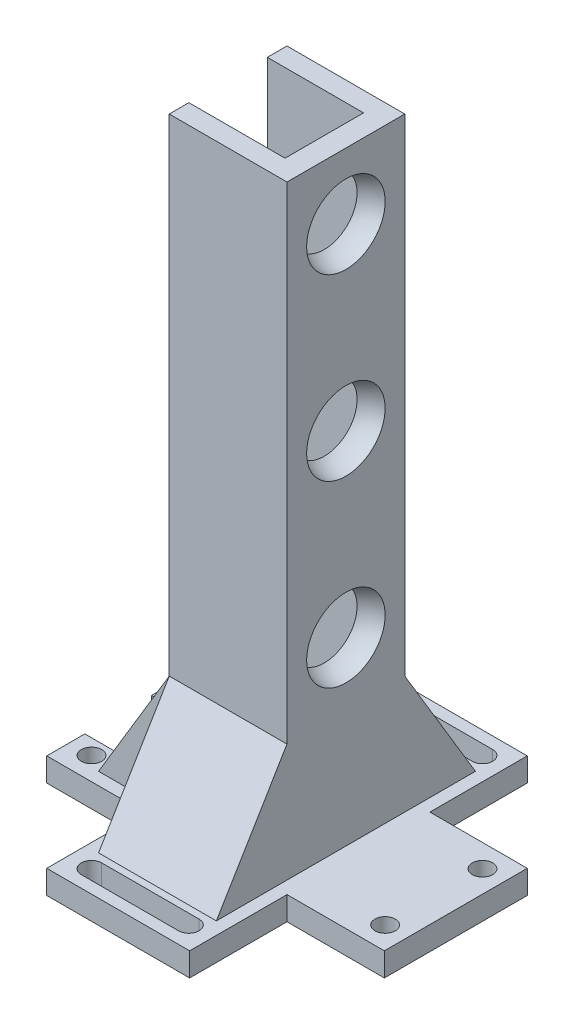
SolidWorks part; units mm, degrees
ref_plane "前视基准面" through (0, 0, 0) normal (0, 0, 1) x (1, 0, 0)
ref_plane "上视基准面" through (0, 0, 0) normal (0, 1, 0) x (1, 0, 0)
ref_plane "右视基准面" through (0, 0, 0) normal (1, 0, 0) x (0, 0, -1)
other "Configuration Table"
sketch "草图1" plane through (0, 0, 0) normal (0, 1, 0) x (1, 0, 0)
  line L1 (-43, 43) -> (43, 43)
  line L2 (-43, 43) -> (-43, -43)
  line L3 (-43, -43) -> (43, -43)
  line L4 (43, 43) -> (43, -43)
  line L5 (-43, 43) -> (43, -43) construction
  line L6 (-43, -43) -> (43, 43) construction
  point P0 (0, 0)
  dimension "D1" = 86
  dimension "D2" = 86
extrude "凸台-拉伸1" add sketch "草图1" along normal blind 6
sketch "草图2" plane through (0, 0, 0) normal (0, 1, 0) x (1, 0, 0)
  line L1 (-15, 15) -> (15, 15)
  line L2 (-15, 15) -> (-15, -15)
  line L3 (-15, -15) -> (15, -15)
  line L4 (15, 15) -> (15, -15)
  line L5 (-15, 15) -> (15, -15) construction
  line L6 (-15, -15) -> (15, 15) construction
  point P0 (0, 0)
  dimension "D1" = 30
  dimension "D2" = 30
extrude "凸台-拉伸2" add sketch "草图2" along normal blind 160
sketch "草图7" plane through (0, 0, 0) normal (0, 0, 1) x (1, 0, 0)
  line L0 (-15, 36) -> (-33, 6)
  line L1 (-15, 160) -> (-15, 6) construction
  line L2 (-43, 6) -> (43, 6) construction
  line L3 (-33, 6) -> (-15, 6)
  line L4 (-15, 6) -> (-15, 36)
  dimension "D1" = 18
  dimension "D2" = 30
extrude "凸台-拉伸3" add sketch "草图7" along normal up to surface and the other way up to surface up to face at (0, 83, 15) other way up to face at (0, 83, -15)
sketch "草图8" plane through (0, 0, 0) normal (0, 1, 0) x (1, 0, 0)
  line L0 (43, 43) -> (-43, 43) construction
  line L1 (-43, 43) -> (-43, -43) construction
  circle A0 centre (-12.4, 37.4) radius 2.6
  dimension "D2" = 5.2
  dimension "D1" = 5.6
  dimension "D3" = 30.6
extrude "切除-拉伸2" cut sketch "草图8" along normal up to surface (6 mm away) up to face at (0, 6, 0)
mirror "镜向2" about plane through (0, 0, 0) normal (0, 0, 1) of "切除-拉伸2"
sketch "草图11" plane through (0, 0, 0) normal (0, 1, 0) x (1, 0, 0)
  line L12 (43, -18.2) -> (18.2, -18.2)
  line L14 (43, -43) -> (43, 43) construction
  line L16 (18.2, -18.2) -> (18.2, -43)
  line L17 (-43, -43) -> (43, -43) construction
  dimension "D1" = 24.8
  dimension "D2" = 24.8
extrude "切除-拉伸3" cut sketch "草图11" along normal up to surface (5 mm away)
sketch "草图12" plane through (0, 0, 0) normal (0, 0, 1) x (1, 0, 0)
  line L0 (15, 160) -> (15, 6) construction
  line L1 (15, 62) -> (15, 42)
  line L2 (-43, 0) -> (18.2, 0) construction
  arc A0 (15, 62) -> (15, 42) centre (15, 52) ccw
  dimension "D1" = 10
  dimension "D2" = 52
revolve "切除-旋转2" cut sketch "草图12" angle 360 about L1
pattern_linear "阵列(线性)1" count 3 spacing 45.6 along (0, 1, 0) of "切除-旋转2"
mirror "镜向6" about plane through (0, 0, 0) normal (0, 0, 1) of "切除-拉伸3"
mirror "镜向7" about plane through (0, 0, 0) normal (1, 0, 0) of "镜向6", "切除-拉伸3"
mirror "镜向8" about plane through (0, 0, 0) normal (1, 0, 0) of "镜向2", "切除-拉伸2"
pattern_circular "阵列(圆周)1" count 2 every 90 of "切除-拉伸2"
mirror "镜向9" about plane through (0, 0, 0) normal (0, 0, 1) of "阵列(圆周)1"
mirror "镜向10" about plane through (0, 0, 0) normal (1, 0, 0) of "镜向9", "阵列(圆周)1"
sketch "草图15" plane through (0, 0, 0) normal (1, 0, 0) x (0, 0, -1)
  line L7 (-15, 160) -> (-15, 6) construction
  line L8 (-15, 36) -> (-15, 6)
  line L9 (-15, 6) -> (-33, 6)
  line L10 (-18.2, 6) -> (-43, 6) construction
  line L11 (-33, 6) -> (-15, 36)
  dimension "D1" = 18
  dimension "D2" = 30
extrude "凸台-拉伸4" add sketch "草图15" along normal blind 15 and the other way blind 15
mirror "镜向11" about plane through (0, 0, 0) normal (0, 0, 1) of "凸台-拉伸4"
sketch "草图17" plane through (0, 0, 0) normal (1, 0, 0) x (0, 0, -1)
  line L0 (-15, 160) -> (-15, 36) construction
  line L1 (10, 160) -> (-10, 160)
  line L2 (10, 160) -> (10, 6)
  line L3 (10, 6) -> (-10, 6)
  line L4 (-10, 160) -> (-10, 6)
  line L5 (15, 160) -> (15, 36) construction
  line L6 (33, 6) -> (-33, 6) construction
  line L7 (-15, 160) -> (15, 160) construction
  line L8 (-18.2, 0) -> (18.2, 0) construction
  dimension "D1" = 20
  dimension "D2" = 5
  dimension "D3" = 5
  dimension "D4" = 0
  dimension "D5" = 0
  dimension "D6" = 154
  dimension "D7" = 6
extrude "切除-拉伸4" cut sketch "草图17" against normal through all and the other way blind 9.5
sketch "草图19" plane through (0, 0, 0) normal (0, 1, 0) x (1, 0, 0)
  line L0 (-12.4, 40) -> (12.4, 40)
  line L1 (12.4, 40) -> (12.4, 34.8)
  line L2 (12.4, 34.8) -> (-12.4, 34.8)
  line L3 (-12.4, 34.8) -> (-12.4, 40)
  circle A0 centre (-12.4, 37.4) radius 2.6 construction
  circle A1 centre (12.4, 37.4) radius 2.6 construction
extrude "切除-拉伸6" cut sketch "草图19" along normal through all
mirror "镜向12" about plane through (0, 0, 0) normal (0, 0, 1) of "切除-拉伸6"
sketch "草图21" plane through (0, 0, 0) normal (1, 0, 0) x (0, 0, -1)
  line L0 (-8.5, 6) -> (8.5, 6)
  line L1 (33, 6) -> (-33, 6) construction
  line L2 (8.5, 6) -> (8.5, 0)
  line L3 (-18.2, 0) -> (18.2, 0) construction
  line L4 (8.5, 0) -> (-8.5, 0)
  line L5 (-8.5, 0) -> (-8.5, 6)
  line L6 (-15, 160) -> (-15, 36) construction
  line L7 (15, 160) -> (15, 36) construction
  dimension "D1" = 17
  dimension "D2" = 6.5
  dimension "D3" = 6.5
extrude "切除-拉伸8" cut sketch "草图21" against normal through all and the other way blind 9.5
